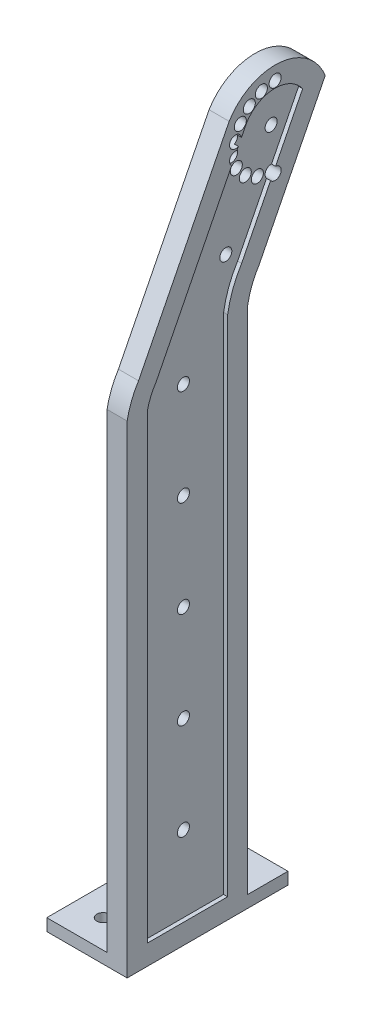
SolidWorks part; units mm, degrees
ref_plane "前视基准面" through (0, 0, 0) normal (0, 0, 1) x (1, 0, 0)
ref_plane "上视基准面" through (0, 0, 0) normal (0, 1, 0) x (1, 0, 0)
ref_plane "右视基准面" through (0, 0, 0) normal (1, 0, 0) x (0, 0, -1)
sketch "草图1" plane through (0, 0, 0) normal (1, 0, 0) x (0, 0, -1)
  line L0 (-15, 0) -> (15, 0)
  line L1 (-15, 0) -> (-15, 120)
  line L2 (15, 0) -> (15, 130)
  line L3 (17.8333, 137.2485) -> (34.2776, 169.8061)
  line L4 (-12.1667, 127.2485) -> (10.3753, 171.8787)
  line L5 (18.3925, 174.3148) -> (21.8127, 164.9179) construction
  line L7 (11.218, 143.9417) -> (10.5417, 142.6028) construction
  line L8 (21.8127, 164.9179) -> (11.9646, 166.6544) construction
  line L9 (13.1525, 169.9179) -> (21.8127, 164.9179) construction
  line L10 (11.9646, 163.1814) -> (21.8127, 164.9179) construction
  line L11 (21.8127, 164.9179) -> (13.1525, 159.9179) construction
  line L12 (21.8127, 164.9179) -> (15.3848, 172.5784) construction
  line L13 (15.3848, 157.2575) -> (21.8127, 164.9179) construction
  line L14 (21.8127, 164.9179) -> (18.3925, 155.521) construction
  line L15 (21.8127, 164.9179) -> (21.8127, 174.9179) construction
  line L16 (21.8127, 154.9179) -> (21.8127, 164.9179) construction
  arc A0 (15, 130) -> (17.8333, 137.2485) centre (34.6882, 126.4823) cw
  arc A1 (-12.1667, 127.2485) -> (-15, 120) centre (4.6882, 116.4823) ccw
  circle A2 centre (0, 23.9341) radius 1.5
  circle A3 centre (0, 47.9341) radius 1.5
  circle A4 centre (0, 71.9341) radius 1.5
  circle A5 centre (0, 95.9341) radius 1.5
  circle A7 centre (21.8127, 164.9179) radius 10 construction
  circle A8 centre (10.5417, 142.6028) radius 1.5
  circle A9 centre (0, 119.9341) radius 1.5
  arc A10 (34.2776, 169.8061) -> (10.3753, 171.8787) centre (21.8127, 164.9179) ccw
  circle A11 centre (21.8127, 164.9179) radius 1.5
  circle A13 centre (11.9646, 166.6544) radius 1.5
  circle A14 centre (11.9646, 163.1814) radius 1.5
  circle A15 centre (13.1525, 159.9179) radius 1.5
  circle A16 centre (15.3848, 157.2575) radius 1.5
  circle A17 centre (18.3925, 155.521) radius 1.5
  circle A18 centre (21.8127, 154.9179) radius 1.5
  circle A19 centre (13.1525, 169.9179) radius 1.5
  circle A20 centre (15.3848, 172.5784) radius 1.5
  circle A21 centre (18.3925, 174.3148) radius 1.5
  circle A22 centre (21.8127, 174.9179) radius 1.5
  point P3 (0, 0)
  dimension "D5" = 20
  dimension "D7" = 20
  dimension "D4" = 3
  dimension "D9" = 3
  dimension "D11" = 3
  dimension "D16" = 20
  dimension "D21" = 20
  dimension "D22" = 20
  dimension "D1" = 30
  dimension "D2" = 120
  dimension "D3" = 130
  dimension "D6" = 24
  dimension "D8" = 25
  dimension "D10" = 15
  dimension "D12" = 25
  dimension "D13" = 24
  dimension "D14" = 24
  dimension "D15" = 24
  dimension "D17" = 20
  dimension "D18" = 20
  dimension "D19" = 20
  dimension "D20" = 20
extrude "凸台-拉伸2" add sketch "草图1" against normal blind 5
ref_plane "基准面1" through (-5, 0, 0) normal (-1, 0, 0) x (0, 0, 1)
ref_plane "基准面3" through (-30, 0, 0) normal (-1, 0, 0) x (0, 0, 1)
ref_plane "基准面5" through (0, 0, 0) normal (1, 0, 0) x (0, 0, -1)
sketch "草图4" plane through (0, 0, 0) normal (1, 0, 0) x (0, 0, -1)
  line L10 (-10, 5) -> (10, 5)
  line L18 (10, 5) -> (10, 130.4183)
  line L19 (13.4775, 139.7151) -> (28.6572, 169.7687)
  line L20 (14.7389, 169.4276) -> (-7.8255, 124.7531)
  line L21 (-10, 119.5247) -> (-10, 5)
  line L22 (-10, 5) -> (10, 5)
  line L23 (10, 5) -> (10, 130.4183)
  line L24 (13.4775, 139.7151) -> (28.6572, 169.7687)
  line L25 (14.7389, 169.4276) -> (-7.8255, 124.7531)
  line L26 (-10, 119.5247) -> (-10, 5)
  arc A6 (13.4775, 139.7151) -> (10, 130.4183) centre (34.6882, 126.4823) ccw
  arc A7 (28.6572, 169.7687) -> (14.7389, 169.4276) centre (21.8127, 164.9179) ccw
  arc A8 (-7.8255, 124.7531) -> (-10, 119.5247) centre (4.6882, 116.4823) ccw
  arc A9 (13.4775, 139.7151) -> (10, 130.4183) centre (34.6882, 126.4823) ccw
  arc A13 (28.6572, 169.7687) -> (14.7389, 169.4276) centre (21.8127, 164.9179) ccw
  arc A14 (-7.8255, 124.7531) -> (-10, 119.5247) centre (4.6882, 116.4823) ccw
  dimension "D1" = 5
extrude "切除-拉伸1" cut sketch "草图4" against normal blind 1
ref_plane "基准面6" through (0, 0, 0) normal (0, -1, 0) x (-1, 0, 0)
sketch "草图5" plane through (0, 0, 0) normal (0, -1, 0) x (-1, 0, 0)
  line L0 (0, -15) -> (20, -15)
  line L1 (20, -15) -> (20, 25)
  line L2 (20, 25) -> (0, 25)
  line L3 (0, 25) -> (0, -15)
  dimension "D1" = 20
  dimension "D2" = 40
  dimension "D3" = 20
extrude "凸台-拉伸3" add sketch "草图5" against normal blind 3
sketch "草图6" plane through (0, 0, 0) normal (0, -1, 0) x (1, 0, 0)
  line L0 (-20, -25) -> (0, -25) construction
  line L1 (-20, 15) -> (0, 15) construction
  line L3 (-20, 15) -> (-20, -25) construction
  circle A0 centre (-13, -18) radius 1.55
  circle A1 centre (-13, 8) radius 1.55
  dimension "D1" = 3.1
  dimension "D4" = 3.1
  dimension "D2" = 7
  dimension "D3" = 7
  dimension "D5" = 7
  dimension "D6" = 7
extrude "切除-拉伸2" cut sketch "草图6" against normal blind 10
